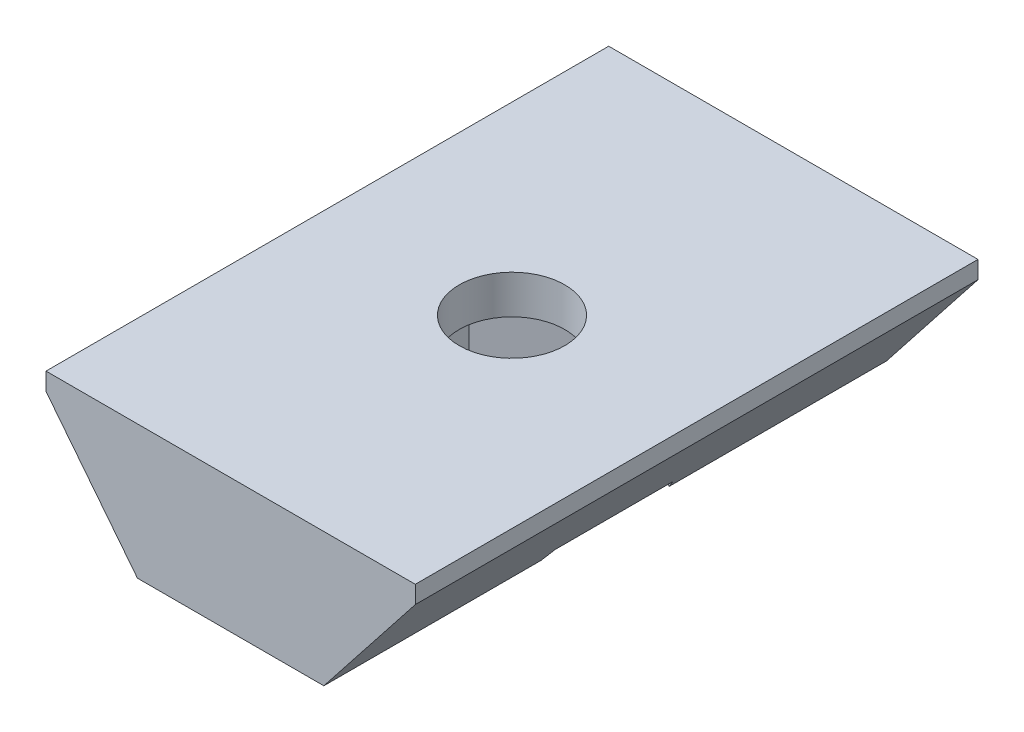
SolidWorks part; units mm, degrees
ref_plane "Plano frontal" through (0, 0, 0) normal (0, 0, 1) x (1, 0, 0)
ref_plane "Plano superior" through (0, 0, 0) normal (0, 1, 0) x (1, 0, 0)
ref_plane "Plano direito" through (0, 0, 0) normal (1, 0, 0) x (0, 0, -1)
sketch "Esboço1" plane through (0, 0, 0) normal (0, 0, 1) x (1, 0, 0)
  line L0 (-2.65, 0) -> (2.65, 0)
  line L1 (-2.65, 0) -> (-5.25, 3.3)
  line L2 (-5.25, 3.8) -> (5.25, 3.8)
  line L3 (5.25, 3.3) -> (2.65, 0)
  line L4 (0, 0) -> (0, 3.8) construction
  line L5 (5.25, 3.3) -> (5.25, 3.8)
  line L6 (-5.25, 3.3) -> (-5.25, 3.8)
  point P3 (0, 0)
  dimension "D1" = 5.3
  dimension "D2" = 10.5
  dimension "D3" = 3.8
  dimension "D4" = 0.5
extrude "Ressalto-extrusão1" add sketch "Esboço1" along normal blind 16
sketch "Esboço2" plane through (0, 3.8, 0) normal (0, 1, 0) x (1, 0, 0)
  line L0 (0, 0) -> (0, -16) construction
  line L1 (5.25, 0) -> (-5.25, 0) construction
  line L2 (5.25, -16) -> (-5.25, -16) construction
  circle A0 centre (0, -8) radius 1.5
  dimension "D1" = 3
extrude "Corte-extrusão1" cut sketch "Esboço2" against normal through all both and the other way through all
sketch "Esboço3" plane through (0, 0, 0) normal (0, -1, 0) x (1, 0, 0)
  line L1 (0, 11.3486) -> (-2.9, 9.6743)
  line L2 (-2.9, 9.6743) -> (-2.9, 6.3257)
  line L3 (-2.9, 6.3257) -> (0, 4.6514)
  line L4 (0, 4.6514) -> (2.9, 6.3257)
  line L5 (2.9, 6.3257) -> (2.9, 9.6743)
  line L6 (2.9, 9.6743) -> (0, 11.3486)
  circle A0 centre (0, 8) radius 2.9 construction
  dimension "D1" = 5.8
extrude "Corte-extrusão2" cut sketch "Esboço3" against normal blind 2.7
